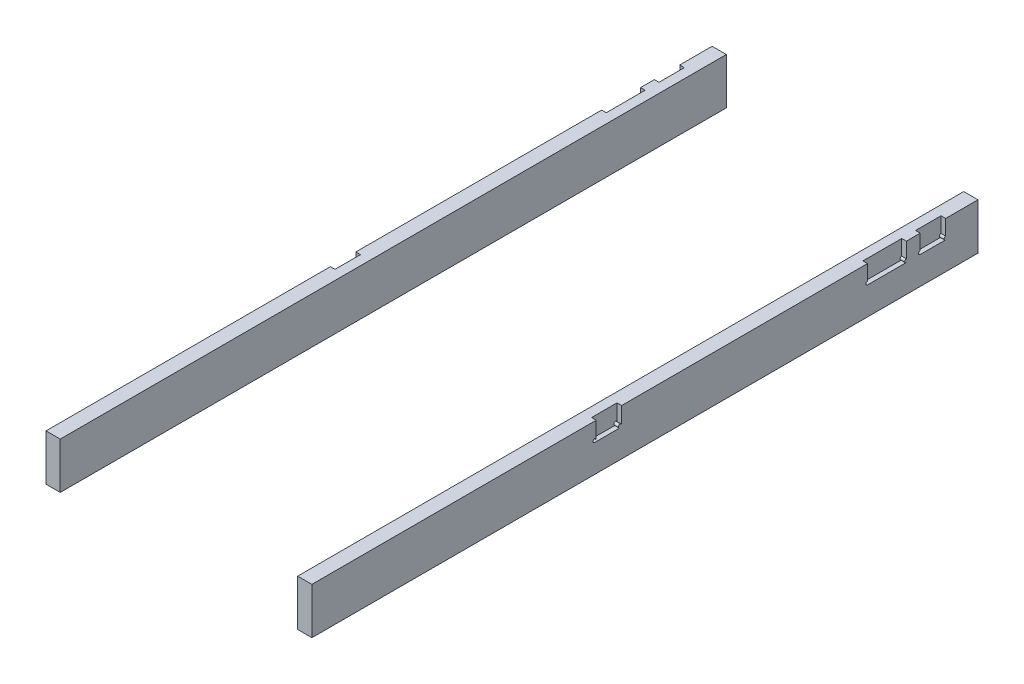
SolidWorks part; units mm, degrees
ref_plane "Front Plane" through (0, 0, 0) normal (0, 0, 1) x (1, 0, 0)
ref_plane "Top Plane" through (0, 0, 0) normal (0, 1, 0) x (1, 0, 0)
ref_plane "Right Plane" through (0, 0, 0) normal (1, 0, 0) x (0, 0, -1)
ref_plane "Plane2" through (-287.55, 0, 0) normal (-1, 0, 0) x (0, 0, 1)
sketch "Sketch8" plane through (-287.55, 0, 0) normal (-1, 0, 0) x (0, 0, 1)
  line L0 (1471.6, -400) -> (30.8, -400)
  line L1 (30.8, -400) -> (30.8, -500)
  line L2 (30.8, -500) -> (1471.6, -500)
  line L3 (1471.6, -500) -> (1471.6, -400)
  dimension "D1" = 100
  dimension "D2" = 1440.8
extrude "Boss-Extrude2" add sketch "Sketch8" against normal blind 30.8 separate body
sketch "Sketch9" plane through (-287.55, 0, 0) normal (-1, 0, 0) x (0, 0, 1)
  line L0 (155.8, -433) -> (155.8, -400)
  line L1 (155.8, -400) -> (100.8, -400)
  line L2 (100.8, -400) -> (100.8, -433)
  line L3 (100.8, -440) -> (155.8, -440)
  line L4 (30.8, -400) -> (30.8, -500) construction
  arc A0 (100.8, -433) -> (100.8, -440) centre (100.8, -436.5) ccw
  arc A1 (155.8, -440) -> (155.8, -433) centre (155.8, -436.5) ccw
  dimension "D1" = 70
extrude "Cut-Extrude4" cut sketch "Sketch9" against normal blind 10
sketch "Sketch10" plane through (-287.55, 0, 0) normal (-1, 0, 0) x (0, 0, 1)
  line L0 (269.79, -433) -> (269.79, -400)
  line L1 (269.79, -400) -> (185.8, -400)
  line L2 (185.8, -400) -> (185.8, -433)
  line L3 (185.8, -440) -> (269.79, -440)
  line L4 (155.8, -433) -> (155.8, -400) construction
  arc A0 (185.8, -433) -> (185.8, -440) centre (185.8, -436.5) cw
  arc A1 (269.79, -440) -> (269.79, -433) centre (269.79, -436.5) ccw
  dimension "D1" = 30
extrude "Cut-Extrude5" cut sketch "Sketch10" against normal blind 10
sketch "Sketch11" plane through (-287.55, 0, 0) normal (-1, 0, 0) x (0, 0, 1)
  line L0 (856.6, -433) -> (856.6, -400)
  line L1 (856.6, -400) -> (801.6, -400)
  line L2 (801.6, -400) -> (801.6, -433)
  line L3 (801.6, -440) -> (856.6, -440)
  line L4 (269.79, -433) -> (269.79, -400) construction
  arc A0 (801.6, -433) -> (801.6, -440) centre (801.6, -436.5) cw
  arc A1 (856.6, -440) -> (856.6, -433) centre (856.6, -436.5) ccw
  dimension "D1" = 531.81
extrude "Cut-Extrude6" cut sketch "Sketch11" against normal blind 10
ref_plane "Plane3" through (287.55, 0, 0) normal (1, 0, 0) x (0, 0, -1)
sketch "Sketch16" plane through (287.55, 0, 0) normal (1, 0, 0) x (0, 0, -1)
  line L0 (-30.8, -400) -> (-1471.6, -400)
  line L1 (-1471.6, -400) -> (-1471.6, -500)
  line L2 (-1471.6, -500) -> (-30.8, -500)
  line L3 (-30.8, -500) -> (-30.8, -400)
  line L6 (-30.8, -400) -> (-30.8, -500) construction
  dimension "D1" = 100
  dimension "D2" = 1440.8
extrude "Boss-Extrude3" add sketch "Sketch16" against normal blind 30.8 separate body
sketch "Sketch17" plane through (287.55, 0, 0) normal (1, 0, 0) x (0, 0, -1)
  line L0 (-856.6, -400) -> (-856.6, -436.4755)
  line L1 (-860.0999, -440) -> (-805.0999, -440)
  line L2 (-801.6, -436.4755) -> (-801.6, -400)
  line L3 (-801.6, -400) -> (-856.6, -400)
  line L4 (-30.8, -500) -> (-30.8, -400) construction
  line L5 (-30.8, -400) -> (-1471.6, -400) construction
  arc A0 (-856.6, -436.4755) -> (-860.0999, -440) centre (-860.0999, -436.5) ccw
  arc A1 (-805.0999, -440) -> (-801.6, -436.4755) centre (-805.0999, -436.5) cw
  dimension "D4" = 3.5
  dimension "D7" = 3.5
  dimension "D1" = 825.8
  dimension "D2" = 55
  dimension "D3" = 40
  dimension "D5" = 36.5
  dimension "D6" = 36.5
extrude "Cut-Extrude7" cut sketch "Sketch17" against normal blind 10
sketch "Sketch18" plane through (287.55, 0, 0) normal (1, 0, 0) x (0, 0, -1)
  line L0 (-269.79, -400) -> (-269.79, -433)
  line L1 (-269.79, -440) -> (-185.8, -440)
  line L2 (-185.8, -433) -> (-185.8, -400)
  line L3 (-185.8, -400) -> (-269.79, -400)
  line L4 (-801.6, -436.4755) -> (-801.6, -400) construction
  arc A0 (-269.79, -433) -> (-269.79, -440) centre (-269.79, -436.5) ccw
  arc A1 (-185.8, -440) -> (-185.8, -433) centre (-185.8, -436.5) cw
  dimension "D1" = 531.81
extrude "Cut-Extrude8" cut sketch "Sketch18" against normal blind 10
sketch "Sketch19" plane through (287.55, 0, 0) normal (1, 0, 0) x (0, 0, -1)
  line L0 (-155.8, -400) -> (-155.8, -433)
  line L1 (-155.8, -440) -> (-100.8, -440)
  line L2 (-100.8, -433) -> (-100.8, -400)
  line L3 (-100.8, -400) -> (-155.8, -400)
  line L4 (-30.8, -500) -> (-30.8, -400) construction
  arc A0 (-155.8, -433) -> (-155.8, -440) centre (-155.8, -436.5) ccw
  arc A1 (-100.8, -440) -> (-100.8, -433) centre (-100.8, -436.5) cw
  dimension "D1" = 70
extrude "Cut-Extrude9" cut sketch "Sketch19" against normal blind 10
